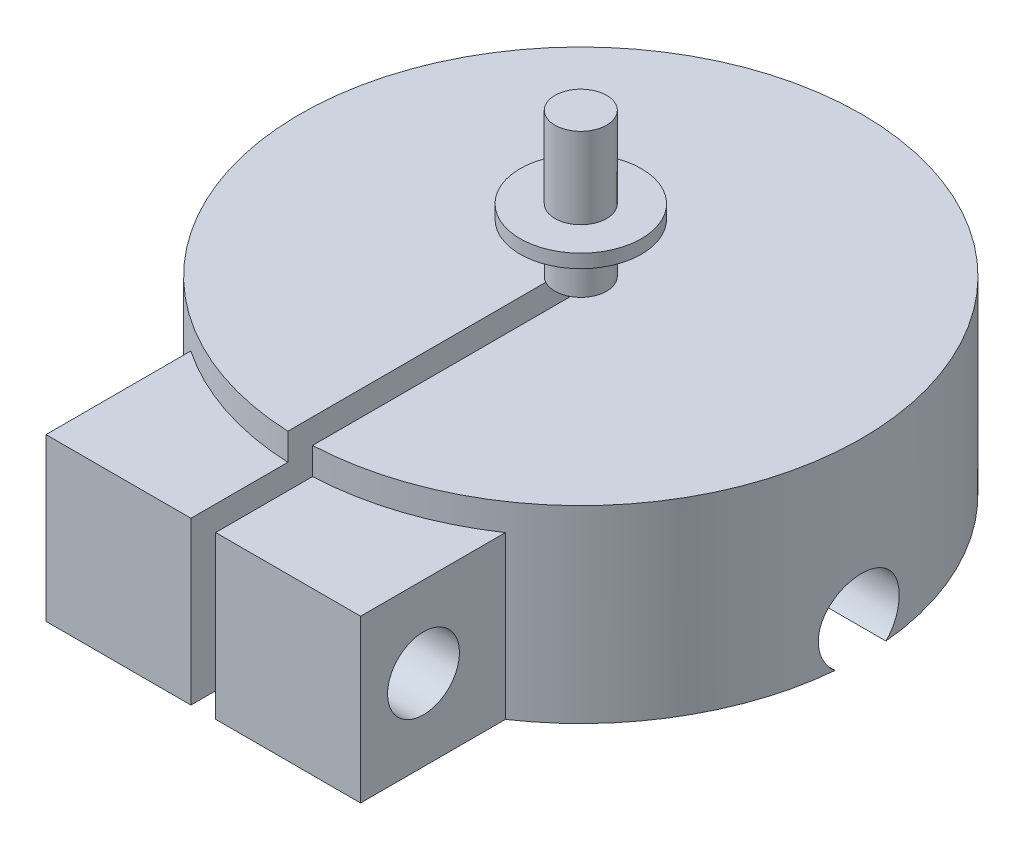
SolidWorks part; units mm, degrees
other "Encoder Shaft Adapter"
ref_plane "Front Plane" through (0, 0, 0) normal (0, 0, 1) x (1, 0, 0)
ref_plane "Top Plane" through (0, 0, 0) normal (0, 1, 0) x (1, 0, 0)
ref_plane "Right Plane" through (0, 0, 0) normal (1, 0, 0) x (0, 0, -1)
sketch3d "Main Profile Sketch datum points"
  point P0 (0, -199.6, 0)
  point P1 (10, -199.6, 0)
  point P2 (0, -199.6, 10)
ref_plane "Main Profile Sketch plane" through (0, -199.6, 0) normal (0, -1, 0) x (-1, 0, 0)
sketch "Main Profile Sketch" plane through (0, -199.6, 0) normal (0, -1, 0) x (-1, 0, 0)
  circle A0 centre (19.0092, 53.2449) radius 1.15
extrude "Main Extrusion" add sketch "Main Profile Sketch" along normal blind 3.6 separate body
sketch3d "Detail Profile 2 Sketch datum points"
  point P0 (0, -203.2, 0)
  point P1 (10, -203.2, 0)
  point P2 (0, -203.2, 10)
ref_plane "Detail Profile 2 Sketch plane" through (0, -203.2, 0) normal (0, -1, 0) x (-1, 0, 0)
sketch "Detail Profile 2 Sketch" plane through (0, -203.2, 0) normal (0, -1, 0) x (-1, 0, 0)
  circle A0 centre (19.0092, 53.2449) radius 2.7
extrude "Detail Extrusion 2" add sketch "Detail Profile 2 Sketch" along normal blind 0.6
sketch3d "Detail Profile 3 Sketch datum points"
  point P0 (0, -203.8, 0)
  point P1 (10, -203.8, 0)
  point P2 (0, -203.8, 10)
ref_plane "Detail Profile 3 Sketch plane" through (0, -203.8, 0) normal (0, -1, 0) x (-1, 0, 0)
sketch "Detail Profile 3 Sketch" plane through (0, -203.8, 0) normal (0, -1, 0) x (-1, 0, 0)
  circle A0 centre (19.0092, 53.2449) radius 1.15
extrude "Detail Extrusion 3" add sketch "Detail Profile 3 Sketch" along normal blind 2.2
sketch3d "Detail Profile 4 Sketch datum points"
  point P0 (0, -206, 0)
  point P1 (10, -206, 0)
  point P2 (0, -206, 10)
ref_plane "Detail Profile 4 Sketch plane" through (0, -206, 0) normal (0, -1, 0) x (-1, 0, 0)
sketch "Detail Profile 4 Sketch" plane through (0, -206, 0) normal (0, -1, 0) x (-1, 0, 0)
  line L0 (18.4592, 53.2449) -> (18.4592, 40.757)
  line L1 (18.4592, 53.2449) -> (19.5592, 53.2449)
  line L2 (19.5592, 53.2449) -> (19.5592, 40.757)
  arc A0 (19.5592, 40.757) -> (18.4592, 40.757) centre (19.0092, 53.2449) ccw
extrude "Detail Extrusion 4" add sketch "Detail Profile 4 Sketch" along normal blind 1.2
sketch3d "Detail Profile 5 Sketch datum points"
  point P0 (0, -207.2, 0)
  point P1 (10, -207.2, 0)
  point P2 (0, -207.2, 10)
ref_plane "Detail Profile 5 Sketch plane" through (0, -207.2, 0) normal (0, -1, 0) x (-1, 0, 0)
sketch "Detail Profile 5 Sketch" plane through (0, -207.2, 0) normal (0, -1, 0) x (-1, 0, 0)
  line L0 (12.0092, 42.8887) -> (12.0092, 36.4449)
  line L1 (12.0092, 36.4449) -> (18.4592, 36.4449)
  line L2 (18.4592, 53.2449) -> (18.4592, 36.4449)
  line L3 (18.4592, 53.2449) -> (19.5592, 53.2449)
  line L4 (19.5592, 53.2449) -> (19.5592, 36.4449)
  line L5 (19.5592, 36.4449) -> (26.0092, 36.4449)
  line L6 (26.0092, 42.8887) -> (26.0092, 36.4449)
  arc A0 (26.0092, 42.8887) -> (12.0092, 42.8887) centre (19.0092, 53.2449) ccw
extrude "Detail Extrusion 5" add sketch "Detail Profile 5 Sketch" along normal blind 2.8
sketch3d "Detail Profile 6 Sketch datum points"
  point P0 (0, -210, 0)
  point P1 (10, -210, 0)
  point P2 (0, -210, 10)
ref_plane "Detail Profile 6 Sketch plane" through (0, -210, 0) normal (0, -1, 0) x (-1, 0, 0)
sketch "Detail Profile 6 Sketch" plane through (0, -210, 0) normal (0, -1, 0) x (-1, 0, 0)
  line L0 (12.0092, 42.8887) -> (12.0092, 36.4449)
  line L1 (12.0092, 36.4449) -> (18.4592, 36.4449)
  line L2 (18.4592, 44.2617) -> (18.4592, 36.4449)
  line L3 (19.5592, 44.2617) -> (19.5592, 36.4449)
  line L4 (19.5592, 36.4449) -> (26.0092, 36.4449)
  line L5 (26.0092, 42.8887) -> (26.0092, 36.4449)
  arc A0 (19.5592, 44.2617) -> (18.4592, 44.2617) centre (19.0092, 53.2449) ccw
  arc A1 (26.0092, 42.8887) -> (12.0092, 42.8887) centre (19.0092, 53.2449) ccw
extrude "Detail Extrusion 6" add sketch "Detail Profile 6 Sketch" along normal blind 4.4
sketch3d "Adapter Cross Bore 1 profile datum points"
  point P0 (-33.0092, -213, -53.2449)
  point P1 (-33.0092, -203, -53.2449)
  point P2 (-33.0092, -213, -43.2449)
ref_plane "Adapter Cross Bore 1 profile plane" through (-33.0092, 0, 0) normal (1, 0, 0) x (0, 0, -1)
sketch "Adapter Cross Bore 1 profile" plane through (-33.0092, 0, 0) normal (1, 0, 0) x (0, 0, -1)
  circle A0 centre (53.2449, -213) radius 1.8
extrude "Adapter Cross Bore 1" cut sketch "Adapter Cross Bore 1 profile" along normal blind 28
sketch3d "Adapter Cross Bore 2 profile datum points"
  point P0 (-27.0092, -210.8, -39.2449)
  point P1 (-27.0092, -200.8, -39.2449)
  point P2 (-27.0092, -210.8, -29.2449)
ref_plane "Adapter Cross Bore 2 profile plane" through (-27.0092, 0, 0) normal (1, 0, 0) x (0, 0, -1)
sketch "Adapter Cross Bore 2 profile" plane through (-27.0092, 0, 0) normal (1, 0, 0) x (0, 0, -1)
  circle A0 centre (39.2449, -210.8) radius 1.6
extrude "Adapter Cross Bore 2" cut sketch "Adapter Cross Bore 2 profile" along normal blind 16
